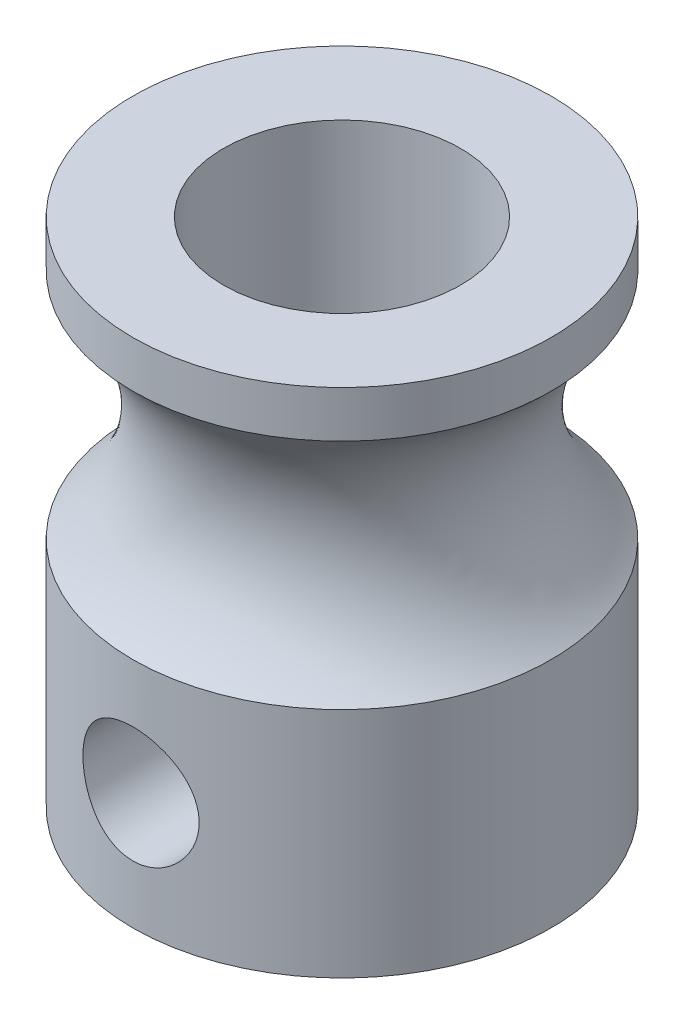
SolidWorks part; units mm, degrees
material "acero"
ref_plane "Alzado" through (0, 0, 0) normal (0, 0, 1) x (1, 0, 0)
ref_plane "Planta" through (0, 0, 0) normal (0, 1, 0) x (1, 0, 0)
ref_plane "Vista lateral" through (0, 0, 0) normal (1, 0, 0) x (0, 0, -1)
sketch "Croquis1" plane through (0, 0, 0) normal (0, 1, 0) x (1, 0, 0)
  circle A0 centre (0, 0) radius 4.5
  circle A1 centre (0, 0) radius 2.55
  dimension "D1" = 9
  dimension "D2" = 5.1
extrude "Saliente-Extruir1" add sketch "Croquis1" along normal blind 11
sketch "Croquis3" plane through (0, 0, 0) normal (1, 0, 0) x (0, 0, -1)
  line L0 (0, 11) -> (0, 0) construction
  line L1 (2.55, 11) -> (-2.55, 11) construction
  line L2 (-4.5, 11) -> (-4.5, 10) construction
  line L3 (-4.5, 11) -> (-4.5, 0) construction
  line L4 (-4.5, 11) -> (-4.5, 0) construction
  line L5 (-4.5, 11) -> (-4.5, 0) construction
  line L7 (-4.5, 0) -> (4.5, 0) construction
  circle A0 centre (-6.6424, 7.5) radius 3.2924
  point P12 (-4.5, 5)
  dimension "D2" = 5
  dimension "D3" = 6.7
  dimension "D1" = 1
revolve "Cortar-Revolución1" cut sketch "Croquis3" angle 360 about L0
ref_plane "Plano1" through (0, 10, 0) normal (0, -1, 0) x (-1, 0, 0)
ref_plane "Plano2" through (0, 5, 0) normal (0, -1, 0) x (-1, 0, 0)
ref_plane "Plano3" through (0, 7.5, 0) normal (0, -1, 0) x (-1, 0, 0)
hole_wizard "Taladro roscado M31" positions "Croquis6" profile "Croquis5" tap size "M3" standard "ISO"
sketch "Croquis6" plane through (0, 0, 0) normal (0, 0, 1) x (1, 0, 0)
  line L0 (0, 0) -> (0, 5) construction
  line L2 (-4.5, 5) -> (4.5, 5) construction
  point P0 (0, 2.5)
cosmetic thread "Rosca de taladro2" parameters "D2"=3
sketch "Croquis5" plane through (0, 2.5, 0) normal (1, 0, 0) x (0, 1, 0)
  line L0 (0, 0) -> (0, 4.5)
  line L1 (0, 4.5) -> (1.25, 4.5)
  line L2 (1.25, 4.5) -> (1.25, 0)
  line L5 (1.25, 0) -> (0, 0)
  line L11 (0, -6.35) -> (0, 107.95) construction
  dimension "Diámetro de perforador para roscar hasta el siguiente" = 2.5
  dimension "Profundidad de perforador para roscar hasta el siguiente" = 4.5
